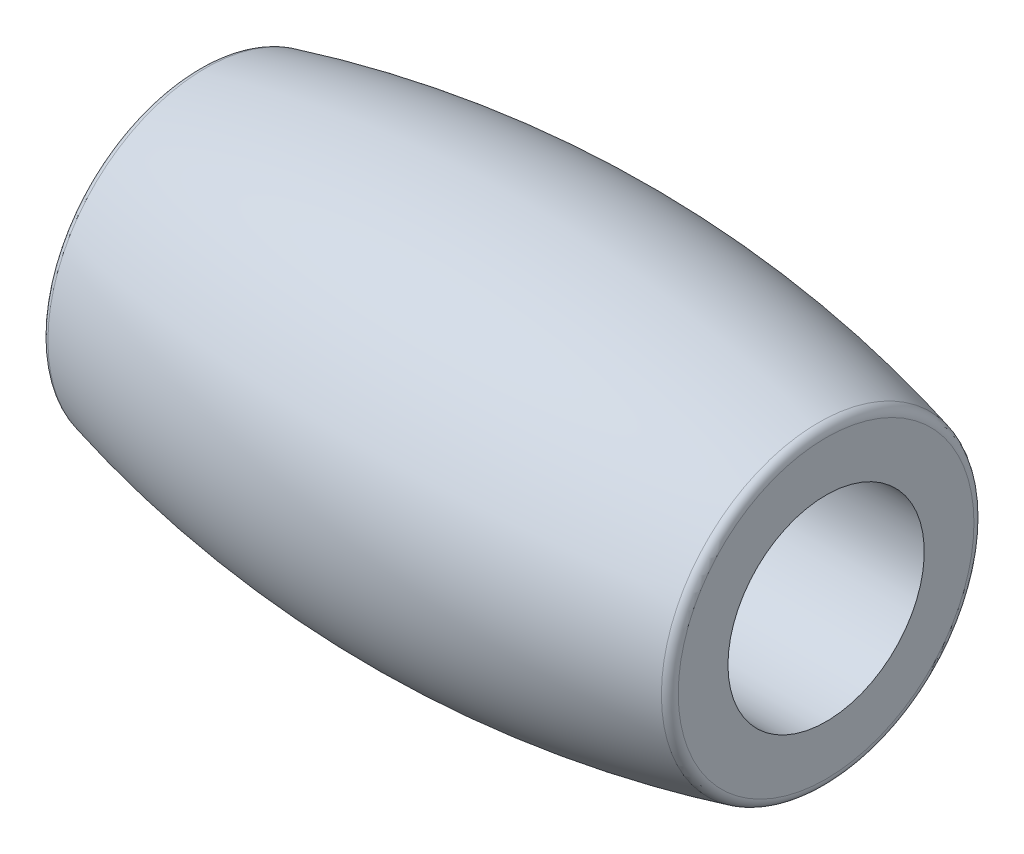
SolidWorks part; units mm, degrees
material "PVC Rigid"
ref_plane "Front Plane" through (0, 0, 0) normal (0, 0, 1) x (1, 0, 0)
ref_plane "Top Plane" through (0, 0, 0) normal (0, 1, 0) x (1, 0, 0)
ref_plane "Right Plane" through (0, 0, 0) normal (1, 0, 0) x (0, 0, -1)
sketch "Sketch1" plane through (0, 0, 0) normal (0, 0, 1) x (1, 0, 0)
  line L0 (-16, 52.5) -> (28.6144, 52.5) construction
  line L1 (-16, 52.5) -> (-16, 57.5) construction
  line L3 (16, 57.5) -> (16, 60.4173)
  line L4 (-16, 57.5) -> (-16, 60.4173)
  line L5 (0, 62.5) -> (0, 52.5) construction
  line L6 (-16, 57.5) -> (16, 57.5)
  arc A0 (16, 60.4173) -> (-16, 60.4173) centre (0, 0) ccw
revolve "Revolve2" add sketch "Sketch1" angle 360 mid plane about L0
fillet "Fillet1" radius 0.5 2 edges at (16, 52.5, 7.9173) (-16, 52.5, 7.9173)
